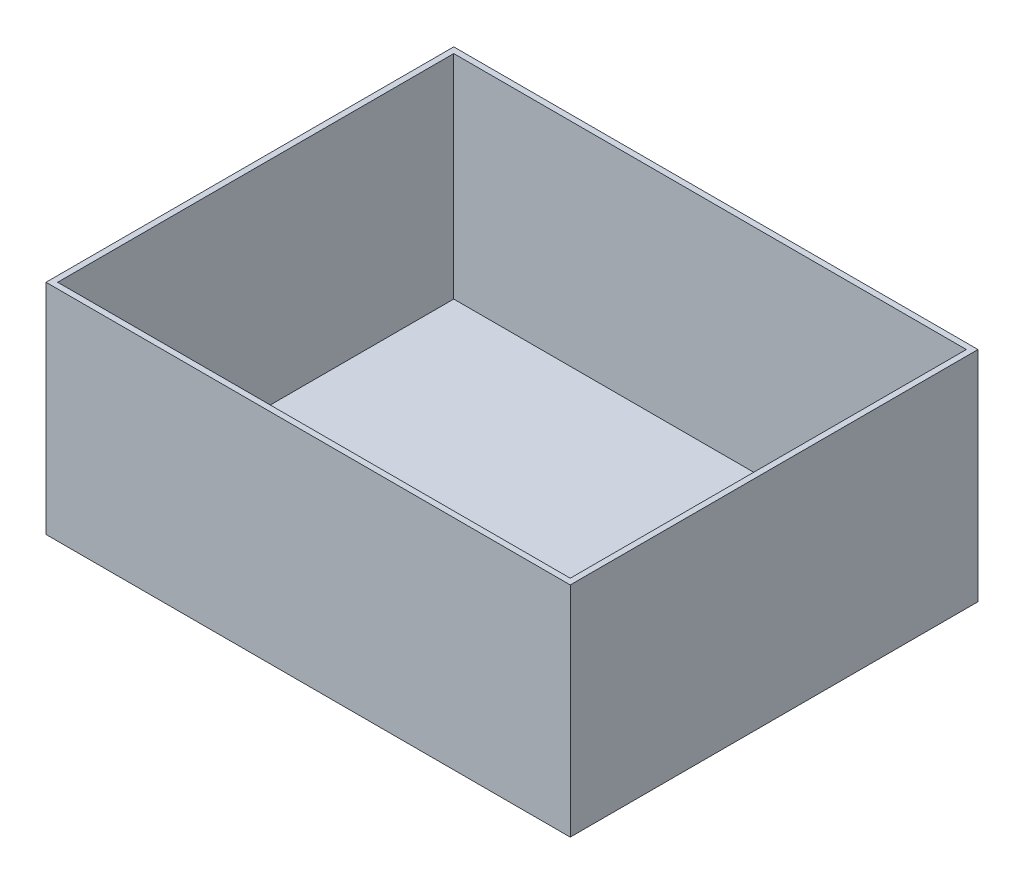
SolidWorks part; units mm, degrees
ref_plane "Front Plane" through (0, 0, 0) normal (0, 0, 1) x (1, 0, 0)
ref_plane "Top Plane" through (0, 0, 0) normal (0, 1, 0) x (1, 0, 0)
ref_plane "Right Plane" through (0, 0, 0) normal (1, 0, 0) x (0, 0, -1)
sketch "Sketch2" plane through (0, 0, 0) normal (0, 1, 0) x (1, 0, 0)
  line L1 (-114.3, 88.9) -> (114.3, 88.9)
  line L2 (-114.3, 88.9) -> (-114.3, -88.9)
  line L3 (-114.3, -88.9) -> (114.3, -88.9)
  line L4 (114.3, 88.9) -> (114.3, -88.9)
  line L5 (-114.3, 88.9) -> (114.3, -88.9) construction
  line L6 (-114.3, -88.9) -> (114.3, 88.9) construction
  point P0 (0, 0)
  dimension "D1" = 177.8
  dimension "D2" = 228.6
extrude "Boss-Extrude1" add sketch "Sketch2" along normal blind 95.25
shell "Shell3" thickness 2.54
